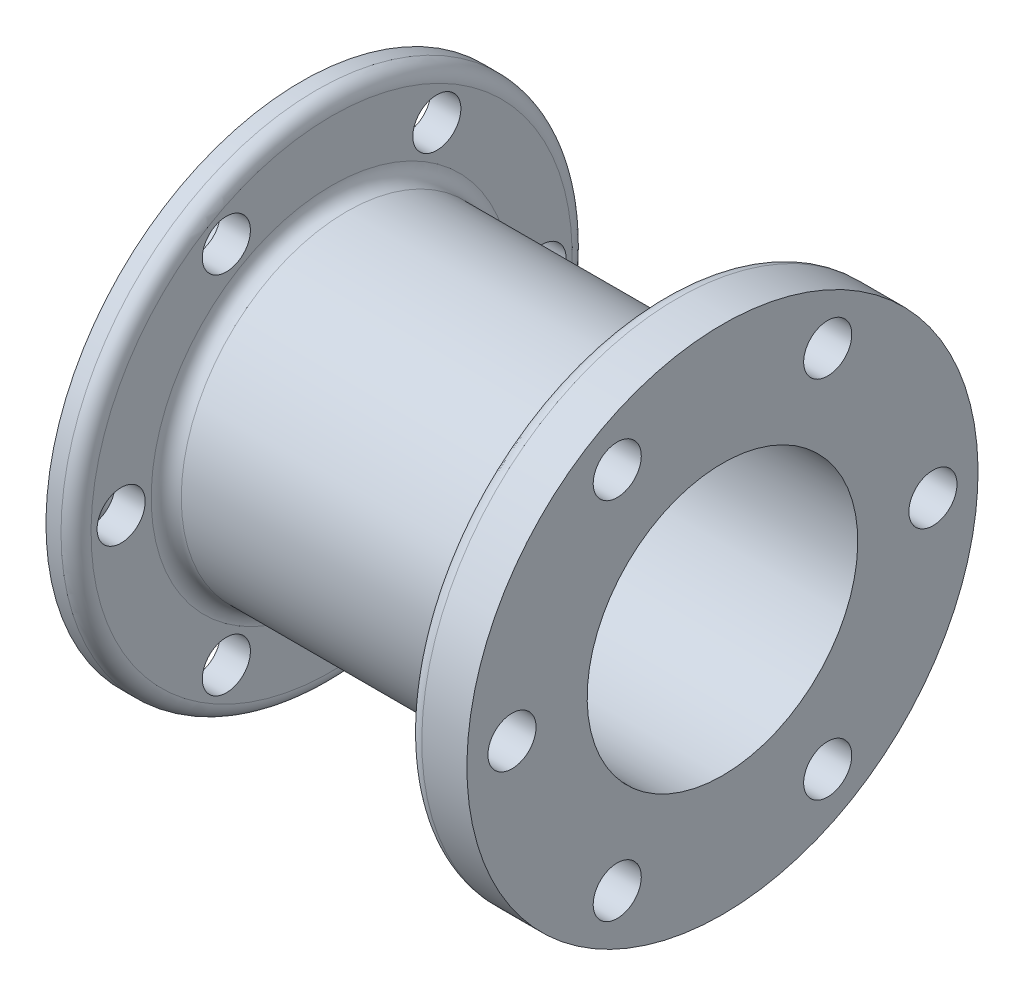
SolidWorks part; units mm, degrees
ref_plane "Front Plane" through (0, 0, 0) normal (0, 0, 1) x (1, 0, 0)
ref_plane "Top Plane" through (0, 0, 0) normal (0, 1, 0) x (1, 0, 0)
ref_plane "Right Plane" through (0, 0, 0) normal (1, 0, 0) x (0, 0, -1)
sketch "Sketch1" plane through (0, 0, 0) normal (0, 0, 1) x (1, 0, 0)
  line L0 (-80, 0) -> (80, 0) construction
  line L1 (-80, 55) -> (-80, 50)
  line L2 (-80, 55) -> (-60, 55)
  line L3 (-60, 55) -> (-60, 85)
  line L4 (-60, 85) -> (-50, 85)
  line L5 (-50, 85) -> (-50, 55)
  line L6 (-50, 55) -> (60, 55)
  line L7 (60, 55) -> (60, 85)
  line L8 (60, 85) -> (80, 85)
  line L9 (-75, 45) -> (80, 45)
  line L10 (80, 45) -> (80, 85)
  line L11 (-80, 50) -> (-80, 39)
  line L12 (-80, 39) -> (-75, 39)
  line L13 (-75, 39) -> (-75, 45)
  point P4 (0, 0)
  dimension "D1" = 160
  dimension "D2" = 20
  dimension "D3" = 10
  dimension "D4" = 20
  dimension "D5" = 10
  dimension "D6" = 10
  dimension "D7" = 90
  dimension "D9" = 170
  dimension "D10" = 5
  dimension "D11" = 78
revolve "Revolve1" add sketch "Sketch1" angle 360 about L0
fillet "Fillet1" radius 5 4 edges at (60, -55, 0) (-50, -55, 0) (60, -85, 0) (-50, -85, 0)
sketch "Sketch2" plane through (-50, 0, 0) normal (1, 0, 0) x (0, 0, -1)
  circle A0 centre (0, 0) radius 70 construction
  circle A1 centre (70, 0) radius 8
  circle A2 centre (35, -60.6218) radius 8
  circle A3 centre (-35, -60.6218) radius 8
  circle A4 centre (-70, 0) radius 8
  circle A5 centre (-35, 60.6218) radius 8
  circle A6 centre (35, 60.6218) radius 8
  point P18 (0, 0)
  dimension "D1" = 140
  dimension "D2" = 16
  dimension "D3" = 6
extrude "Cut-Extrude1" cut sketch "Sketch2" against normal through all both and the other way through all
